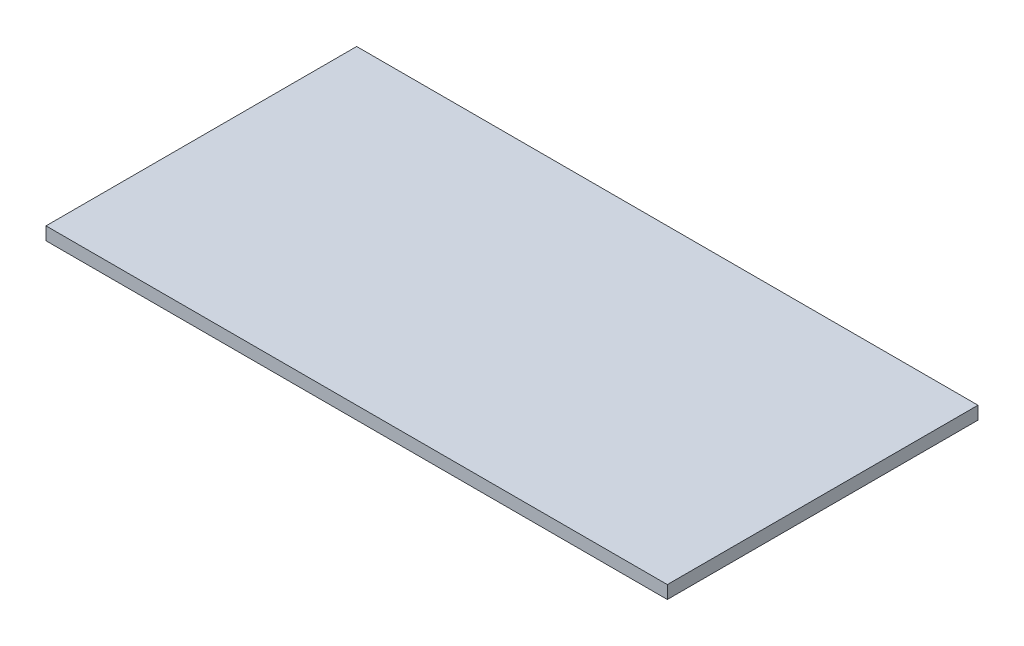
SolidWorks part; units mm, degrees
ref_plane "Front Plane" through (0, 0, 0) normal (0, 0, 1) x (1, 0, 0)
ref_plane "Top Plane" through (0, 0, 0) normal (0, 1, 0) x (1, 0, 0)
ref_plane "Right Plane" through (0, 0, 0) normal (1, 0, 0) x (0, 0, -1)
sketch "Sketch1" plane through (0, 0, 0) normal (0, 1, 0) x (1, 0, 0)
  line L1 (0, 0) -> (152.4, 0)
  line L2 (0, 0) -> (0, 76.2)
  line L3 (0, 76.2) -> (152.4, 76.2)
  line L4 (152.4, 0) -> (152.4, 76.2)
  dimension "D1" = 152.4
  dimension "D2" = 76.2
extrude "Boss-Extrude1" add sketch "Sketch1" along normal blind 3.175
